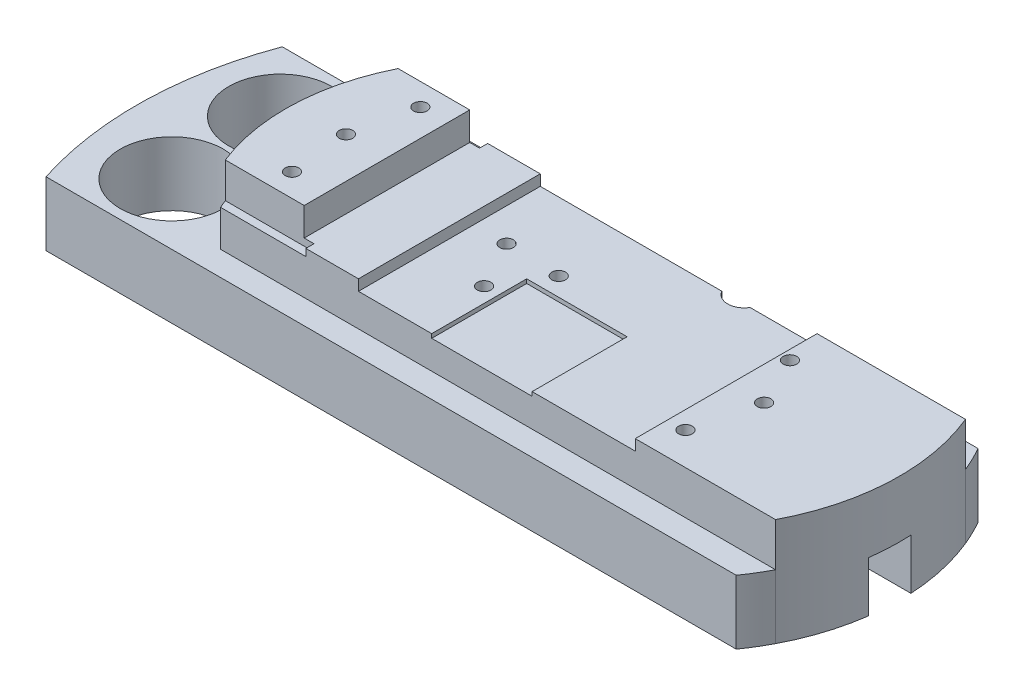
SolidWorks part; units mm, degrees
ref_plane "Front Plane" through (0, 0, 0) normal (0, 0, 1) x (1, 0, 0)
ref_plane "Top Plane" through (0, 0, 0) normal (0, 1, 0) x (1, 0, 0)
ref_plane "Right Plane" through (0, 0, 0) normal (1, 0, 0) x (0, 0, -1)
sketch "Sketch1" plane through (0, 0, 0) normal (0, 1, 0) x (1, 0, 0)
  line L1 (-110, -33.5) -> (110, -33.5)
  line L2 (-110, -33.5) -> (-110, 33.5)
  line L3 (-110, 33.5) -> (110, 33.5)
  line L4 (110, -33.5) -> (110, 33.5)
  line L5 (-110, -33.5) -> (110, 33.5) construction
  line L6 (-110, 33.5) -> (110, -33.5) construction
  point P0 (0, 0)
  dimension "D1" = 67
  dimension "D2" = 220
extrude "Boss-Extrude1" add sketch "Sketch1" along normal blind 50
sketch "Sketch2" plane through (0, 0, 0) normal (0, -1, 0) x (1, 0, 0)
  line L0 (-110, -33.5) -> (-110, 33.5) construction
  line L1 (110, 33.5) -> (110, -33.5) construction
  line L2 (110, 33.5) -> (101, 33.5)
  line L3 (-110, 33.5) -> (110, 33.5) construction
  line L4 (110, -33.5) -> (104, -33.5)
  line L5 (110, -33.5) -> (-110, -33.5) construction
  line L6 (-110, 33.5) -> (-103.5, 33.5)
  line L7 (-110, -33.5) -> (-100.5, -33.5)
  circle A0 centre (30.5922, -3.2198) radius 79.4078
  circle A1 centre (-35.1589, 2.9929) radius 74.8411
  line M7 (110, -33.5) -> (110, 33.5)
  line M8 (110, 33.5) -> (-110, 33.5)
  line M9 (-110, 33.5) -> (-110, -33.5)
  line M10 (-110, -33.5) -> (110, -33.5)
  dimension "D1" = 9
  dimension "D2" = 6
  dimension "D3" = 6.5
  dimension "D4" = 9.5
extrude "Cut-Extrude1" cut sketch "Sketch2" against normal through all contours A0 M7 M8 | A0 M10 M7 | A1 M9 M10 | A1 M8 M9
sketch "Sketch3" plane through (0, 0, 33.5) normal (0, 0, -1) x (-1, 0, 0)
  line L0 (110, 50) -> (75.7, 50)
  line L2 (75.7, 50) -> (75.7, 39.6)
  line L3 (75.7, 39.6) -> (52.7, 39.6)
  line L4 (52.7, 39.6) -> (52.7, 35.6)
  line L5 (52.7, 35.6) -> (-49.3, 35.6)
  line L6 (-104, 50) -> (100.5, 50) construction
  line L10 (110, 0) -> (110, 50) construction
  line L11 (-49.3, 35.6) -> (-49.3, 39.6)
  line L12 (-49.3, 39.6) -> (-110, 39.6)
  line L13 (-110, 50) -> (-110, 0) construction
  line L14 (-110, 39.6) -> (-110, 50)
  line L15 (-110, 50) -> (75.7, 50)
  line M13 (-101, 0) -> (-101, 50)
  line M14 (-101, 50) -> (103.5, 50)
  dimension "D1" = 10.4
  dimension "D2" = 34.3
  dimension "D3" = 23
  dimension "D4" = 4
  dimension "D5" = 102
extrude "Cut-Extrude2" cut sketch "Sketch3" along normal through all contours L11 L12 L2 L3 L4 L5 M13 M14
sketch "Sketch4" plane through (0, 50, 0) normal (0, 1, 0) x (1, 0, 0)
  line L0 (-72.0873, 33.5) -> (-72.0873, 30.5)
  line L1 (-75.7, 33.5) -> (-100.5, 33.5) construction
  line L2 (-72.0873, 30.5) -> (-102.0873, 30.5)
  line L3 (-72.0873, -33.5) -> (-72.0873, -30.5)
  line L4 (-103.5, -33.5) -> (-75.7, -33.5) construction
  line L5 (-72.0873, -30.5) -> (-104.7617, -30.5)
  line L6 (-72.0873, 33.5) -> (-75.7, 33.5)
  line L7 (-72.0873, -33.5) -> (-75.7, -33.5)
  arc A0 (-100.5, 33.5) -> (-103.5, -33.5) centre (-35.1589, -2.9929) ccw construction
  line M5 (-103.5, -33.5) -> (-75.7, -33.5)
  line M6 (-75.7, -33.5) -> (-75.7, 33.5)
  line M7 (-75.7, 33.5) -> (-100.5, 33.5)
  arc M8 (-100.5, 33.5) -> (-103.5, -33.5) centre (-35.1589, -2.9929) ccw
  dimension "D1" = 3
  dimension "D2" = 3
  dimension "D3" = 30
extrude "Cut-Extrude3" cut sketch "Sketch4" against normal blind 13 contours L2 M6 M7 M8 | L0 L6 L2 M6 | L5 M6 M8 M5 | L7 L3 L5 M6
sketch "Sketch6" plane through (0, 0, 0) normal (0, -1, 0) x (1, 0, 0)
  line L0 (-75.7, -33.5) -> (-110, -33.5)
  line L1 (104, -33.5) -> (-100.5, -33.5) construction
  line L2 (-75.7, -33.5) -> (-75.7, 33.5)
  line L3 (-103.5, 33.5) -> (101, 33.5) construction
  line L4 (-75.7, -9) -> (-40.6, -9) construction
  line L5 (-75.7, 8.7) -> (-31.2, 8.7) construction
  line L6 (-75.7, -8.3) -> (-20.7, -8.3) construction
  line L8 (104, -33.5) -> (-100.5, -33.5) construction
  line L9 (-110, -33.5) -> (-110, 33.5)
  line L10 (-110, 33.5) -> (-75.7, 33.5)
  circle A0 centre (-40.6, -9) radius 2.5
  circle A1 centre (-31.2, 8.7) radius 2.5
  circle A2 centre (61.6, -1.7) radius 2.5
  circle A3 centre (55.8, 21.5) radius 2.5
  circle A4 centre (52.8, -20) radius 2.5
  circle A5 centre (-20.7, -8.3) radius 2.5
  circle A6 centre (-88.7, 22) radius 2.5
  circle A7 centre (-90.7, 0.1) radius 2.5
  circle A8 centre (-85.7, -22.3) radius 2.5
  arc A10 (-103.5, 33.5) -> (-100.5, -33.5) centre (-35.1589, 2.9929) ccw construction
  dimension "D2" = 5
  dimension "D3" = 35.1
  dimension "D4" = 34.3
  dimension "D5" = 44.5
  dimension "D6" = 24.5
  dimension "D7" = 55
  dimension "D8" = 42.2
  dimension "D9" = 137.3
  dimension "D10" = 128.5
  dimension "D11" = 131.5
  dimension "D12" = 10
  dimension "D13" = 15
  dimension "D14" = 13
  dimension "D15" = 11.2
  dimension "D16" = 33.6
  dimension "D17" = 55.5
  dimension "D18" = 31.8
  dimension "D19" = 55
  dimension "D20" = 13.5
  dimension "D21" = 25.2
extrude "Cut-Extrude4" cut sketch "Sketch6" against normal through all contours A0 | A5 | A1 | A6 | A7 | A8 | A4 | A2 | A3
sketch "Sketch7" plane through (0, 35.6, 0) normal (0, 1, 0) x (1, 0, 0)
  line L1 (-25.7, 1.5) -> (11.3, 1.5)
  line L2 (-25.7, 1.5) -> (-25.7, -33.5)
  line L3 (-25.7, -33.5) -> (11.3, -33.5)
  line L4 (11.3, 1.5) -> (11.3, -33.5)
  line L8 (-75.7, 30.5) -> (-75.7, -30.5) construction
  line L9 (-75.7, 30.5) -> (-75.7, -30.5) construction
  line L10 (-52.7, -33.5) -> (49.3, -33.5) construction
  dimension "D1" = 50
  dimension "D2" = 87
  dimension "D3" = 35
extrude "Cut-Extrude5" cut sketch "Sketch7" against normal blind 1.5
sketch "Sketch8" plane through (0, 50, 0) normal (0, 1, 0) x (1, 0, 0)
  line L0 (-72.0873, -33.5) -> (-110, -33.5)
  line L1 (-110, -33.5) -> (-110, 33.5)
  line L3 (-110, 33.5) -> (19.4, 33.5)
  line L6 (19.4, 36.5) -> (19.4, 30.5)
  line L7 (19.4, 33.5) -> (24.5962, 33.5)
  line L10 (-72.0873, 33.5) -> (-100.5, 33.5) construction
  line L11 (-52.7, 33.5) -> (49.3, 33.5) construction
  circle A1 centre (19.4, 36.5) radius 6
  arc A2 (-102.0873, 30.5) -> (-104.7617, -30.5) centre (-35.1589, -2.9929) ccw construction
  dimension "D1" = 12
  dimension "D2" = 129.4
extrude "Cut-Extrude6" cut sketch "Sketch8" against normal blind 18.5 contours L6 A1 L7 | L3 A1 L6
sketch "Sketch10" plane through (0, 0, 0) normal (0, -1, 0) x (1, 0, 0)
  line L0 (-98.7229, 42.5) -> (95.5176, 42.5)
  line L1 (-1.6027, 42.5) -> (-1.6027, -42.5) construction
  line L2 (99.6042, -42.5) -> (-94.5861, -42.5)
  line L3 (-103.5, 33.5) -> (101, 33.5)
  line L4 (104, -33.5) -> (-100.5, -33.5)
  line L5 (109.9347, 0) -> (-164.9655, 0) construction
  line L6 (-98.7229, 42.5) -> (-158.8436, 42.5)
  line L7 (-94.5861, -42.5) -> (-156.7694, -42.5)
  circle A0 centre (-35.1589, 2.9929) radius 74.8411
  arc A1 (104, -33.5) -> (101, 33.5) centre (30.5922, -3.2198) ccw construction
  circle A2 centre (30.5922, -3.2198) radius 79.4078
  arc A3 (-104.7617, 30.5) -> (-102.0873, -30.5) centre (-35.1589, 2.9929) ccw construction
  circle A9 centre (-35.1589, 2.9929) radius 129.8411
  line M74 (101, 33.5) -> (-103.5, 33.5)
  arc M75 (-103.5, 33.5) -> (-100.5, -33.5) centre (-35.1589, 2.9929) ccw
  line M90 (-100.5, -33.5) -> (104, -33.5)
  dimension "D1" = 85
  dimension "D3" = 42.5
  dimension "D2" = 55
extrude "Boss-Extrude2" add sketch "Sketch10" against normal offset from surface (23.6 mm away) 12 separate body contours A2 L0 A0 M74 | L0 A2 L3 A0 | L3 A9 L0 A0 | A9 A2 L0 M74 | A9 L2 A2 M90 | L2 A9 L4 A0 | L4 A2 L2 A0 | A2 A0 L2 M90 | L6 A9 L7 A0 M75 up to face at (-18.2, 35.6, -8.3)
sketch "Sketch9" plane through (0, 0, 0) normal (0, -1, 0) x (1, 0, 0)
  line L0 (-135, 1) -> (-135, -1) construction
  line L1 (-103.5, 33.5) -> (101, 33.5) construction
  line L2 (-125, -28.5) -> (0, -28.5)
  line L3 (-125, -28.5) -> (-125, 28.5)
  line L4 (-125, 28.5) -> (0, 28.5)
  line L5 (0, -28.5) -> (0, 28.5)
  line L6 (-125, -28.5) -> (0, 28.5) construction
  line L7 (-125, 28.5) -> (0, -28.5) construction
  line L8 (0, 28.5) -> (0, 7.5)
  line L9 (0, -7.5) -> (110, -7.5)
  line L10 (0, -7.5) -> (0, 7.5)
  line L11 (0, 7.5) -> (110, 7.5)
  line L12 (110, -7.5) -> (110, 7.5)
  line L13 (0, -7.5) -> (110, 7.5) construction
  line L14 (0, 7.5) -> (110, -7.5) construction
  line L15 (0, -7.5) -> (0, -28.5)
  circle A1 centre (-135, 20) radius 19
  circle A2 centre (-135, -20) radius 19
  arc A3 (104, -33.5) -> (101, 33.5) centre (30.5922, -3.2198) ccw construction
  circle A4 centre (2.3966, -9.8966) radius 2.3966
  circle A5 centre (2.3966, 9.8966) radius 2.3966
  circle A6 centre (-116.5859, 30.8966) radius 2.3966
  circle A7 centre (-116.5859, -30.8966) radius 2.3966
  circle A8 centre (-127.3966, 0) radius 2.3966
  circle A9 centre (-2.3966, 26.1034) radius 2.3966
  circle A10 centre (-2.3966, -26.1034) radius 2.3966
  point P0 (-62.5, 0)
  point P4 (-135, -1)
  point P5 (-135, 1)
  point P10 (-135, 0)
  point P20 (55, 0)
  circle M1 centre (-20.7, -8.3) radius 2.5
  circle M2 centre (-31.2, 8.7) radius 2.5
  circle M3 centre (-88.7, 22) radius 2.5
  circle M4 centre (-90.7, 0.1) radius 2.5
  circle M5 centre (-85.7, -22.3) radius 2.5
  circle M7 centre (61.6, -1.7) radius 2.5
  circle M9 centre (-40.6, -9) radius 2.5
  arc M11 (104, -33.5) -> (101, 33.5) centre (30.5922, -3.2198) ccw
  arc M13 (-103.5, 33.5) -> (-100.5, -33.5) centre (-35.1589, 2.9929) ccw
  dimension "D2" = 38
  dimension "D4" = 2
  dimension "D5" = 135
  dimension "D6" = 5
  dimension "D7" = 10
  dimension "D8" = 15
extrude "Cut-Extrude7" cut sketch "Sketch9" against normal offset from surface (18.6 mm away) 5 contours L4 A1 L3 | L3 A2 L2 | A2 L2 L4 A1 L3 M13 | A10 L15 L5 L8 A9 L4 L2 M13 M1 M3 M5 M9 M4 M2 | L11 L5 L9 M11 M7 | A10 | A9 | A5 L5 L11 | A4 L9 L15 | L2 A2 L3 | L3 A1 L4 | A8 L3 A1 | A8 A2 L3 up to face at (-16.785, 23.6, -0.0635)
sketch "Sketch12" plane through (0, 0, 0) normal (0, -1, 0) x (1, 0, 0)
  circle A0 centre (-135, -20) radius 19
  circle A1 centre (-135, 20) radius 19
  arc A2 (-128.2482, -2.2401) -> (-118.0074, -28.5) centre (-135, -20) ccw construction
  arc A3 (-118.0074, 28.5) -> (-128.2482, 2.2401) centre (-135, 20) ccw construction
extrude "Cut-Extrude8" cut sketch "Sketch12" against normal up to surface (23.6 mm away)
